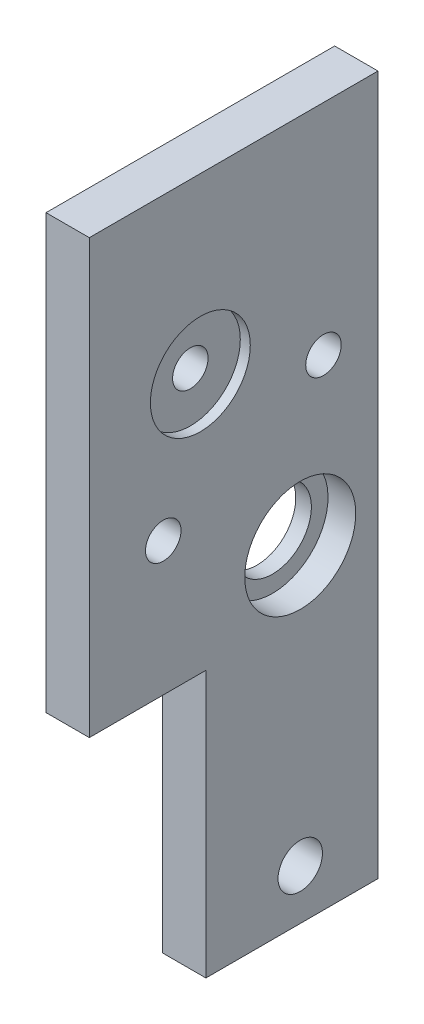
SolidWorks part; units mm, degrees
ref_plane "Front Plane" through (0, 0, 0) normal (0, 0, 1) x (1, 0, 0)
ref_plane "Top Plane" through (0, 0, 0) normal (0, 1, 0) x (1, 0, 0)
ref_plane "Right Plane" through (0, 0, 0) normal (1, 0, 0) x (0, 0, -1)
sketch "Sketch1" plane through (0, 0, 0) normal (1, 0, 0) x (0, 0, -1)
  line L1 (0, 0) -> (-30, 0)
  line L2 (0, 0) -> (0, 63)
  line L3 (0, 63) -> (-30, 63)
  line L4 (-30, 0) -> (-30, 63)
  dimension "D1" = 30
  dimension "D2" = 63
extrude "Boss-Extrude1" add sketch "Sketch1" against normal blind 4
sketch "Sketch2" plane through (0, 0, 0) normal (1, 0, 0) x (0, 0, -1)
  line L0 (-30, 0) -> (0, 0) construction
  line L1 (0, 0) -> (0, 63) construction
  circle A0 centre (-7, 29.5) radius 5
  dimension "D1" = 10
  dimension "D2" = 29.5
  dimension "D3" = 7
extrude "Cut-Extrude1" cut sketch "Sketch2" against normal through all
sketch "Sketch4" [suppressed] plane through (0, 0, 0) normal (1, 0, 0) x (0, 0, -1)
  line L0 (0, 0) -> (0, 57) construction
  line L1 (-15.3544, 38.7) -> (-2.5009, 45.879)
  line L2 (-2.5009, 45.879) -> (-15.1448, 53.421)
  line L3 (-15.1448, 53.421) -> (-15.3544, 38.7)
  circle A0 centre (-11, 46) radius 4.25 construction
  circle A1 centre (-7, 27) radius 5 construction
  dimension "D2" = 19
  dimension "D1" = 8.5
  dimension "D3" = 11
hole_wizard "M4x0.7 Tapped Hole1" [suppressed] positions "3DSketch2" profile "Sketch6" tap size "M4x0.7" standard "ANSI Metric"
sketch3d "3DSketch2" [suppressed]
  point P0 (0, 38.7, 15.3544)
  point P3 (0, 45.879, 2.5009)
  point P6 (0, 53.421, 15.1448)
sketch "Sketch6" plane through (0, 38.7, 15.3544) normal (0, 1, 0) x (0, 0, -1)
  line L0 (0, 0) -> (0, 4)
  line L1 (0, 4) -> (1.05, 4)
  line L3 (1.05, 4) -> (1.05, 2)
  line L4 (1.05, 2) -> (1.65, 2)
  line L5 (1.65, 2) -> (1.65, 0)
  line L7 (1.65, 0) -> (0, 0)
  line L11 (0, -6.35) -> (0, 107.95) construction
  dimension "Thru Tap Drill Dia." = 2.1
  dimension "Thru Tap Drill Depth" = 4
  dimension "Thread Major Dia." = 3.3
  dimension "Thread Depth" = 2
sketch "Sketch7" [suppressed] plane through (-4, 0, 0) normal (-1, 0, 0) x (0, 0, 1)
  line L1 (15.3544, 38.7) -> (15.1448, 53.421)
  line L2 (15.1448, 53.421) -> (2.5009, 45.879)
  line L3 (2.5009, 45.879) -> (15.3544, 38.7)
  circle A0 centre (11, 46) radius 4.25 construction
hole_wizard "CBORE for M3 Pan Head Machine Screw1" [suppressed] positions "3DSketch3" profile "Sketch8" counterbore size "M3" standard "ANSI Metric"
sketch3d "3DSketch3" [suppressed]
  point P0 (-4, 46, 11)
sketch "Sketch8" plane through (-4, 46, 11) normal (0, 1, 0) x (0, 0, 1)
  line L0 (0, 0) -> (0, 4)
  line L1 (0, 4) -> (1.6, 4)
  line L3 (1.6, 4) -> (1.6, 1)
  line L4 (1.6, 1) -> (5.1, 1)
  line L5 (5.1, 1) -> (5.1, 0)
  line L7 (5.1, 0) -> (0, 0)
  line L11 (0, -6.35) -> (0, 107.95) construction
  dimension "Thru Hole Dia." = 3.2
  dimension "Thru Hole Depth" = 4
  dimension "C'Bore Dia." = 10.2
  dimension "C'Bore Depth" = 1
sketch "Sketch10" plane through (0, 0, 0) normal (1, 0, 0) x (0, 0, -1)
  line L0 (0, 0) -> (0, 63) construction
  line L1 (-30, 0) -> (0, 0) construction
  circle A0 centre (-7, 4.5) radius 2
  dimension "D1" = 4
  dimension "D2" = 7
  dimension "D3" = 4.5
hole_wizard "Ø4.0 (4) Diameter Hole1" positions "3DSketch4" profile "Sketch11" hole size "Ø4.0" standard "ANSI Metric" end condition through all
sketch3d "3DSketch4"
  point P0 (0, 4.5, 7)
sketch "Sketch11" plane through (0, 4.5, 7) normal (0, 1, 0) x (0, 0, -1)
  line L0 (0, 0) -> (0, 4)
  line L1 (0, 4) -> (2, 4)
  line L2 (2, 4) -> (2, 0)
  line L5 (2, 0) -> (0, 0)
  line L11 (0, -6.35) -> (0, 107.95) construction
  dimension "Thru Hole Dia." = 4
  dimension "Thru Hole Depth" = 4
sketch "Sketch12" plane through (0, 0, 0) normal (1, 0, 0) x (0, 0, -1)
  line L1 (-30, 0) -> (-15.5, 0)
  line L2 (-30, 0) -> (-30, 24)
  line L3 (-30, 24) -> (-15.5, 24)
  line L4 (-15.5, 0) -> (-15.5, 24)
  dimension "D1" = 14.5
  dimension "D2" = 24
extrude "Cut-Extrude2" cut sketch "Sketch12" against normal through all
mirror "Mirror7" about plane through (0, 0, 0) normal (1, 0, 0) of "Cut-Extrude2", "Cut-Extrude1", "Boss-Extrude1"
sketch "Sketch13" plane through (-4, 0, 0) normal (-1, 0, 0) x (0, 0, 1)
  line L0 (0, 63) -> (30, 63) construction
  line L1 (-5.8164, 63) -> (36.8572, 63)
  line L2 (-5.8164, 63) -> (-5.8164, -2.7798)
  line L3 (-5.8164, -2.7798) -> (36.8572, -2.7798)
  line L4 (36.8572, 63) -> (36.8572, -2.7798)
extrude "Cut-Extrude5" cut sketch "Sketch13" against normal blind 4
sketch "Sketch30" plane through (0, 0, 0) normal (-1, 0, 0) x (0, 0, 1)
  line L0 (0, 0) -> (0, 63) construction
  line L1 (15.5, 0) -> (0, 0) construction
  circle A0 centre (7, 4.5) radius 2
  dimension "D1" = 4
  dimension "D2" = 7
  dimension "D3" = 4.5
hole_wizard "Ø4.0 (4) Diameter Hole6" positions "3DSketch19" profile "Sketch31" hole size "Ø4.0" standard "ANSI Metric" end condition through all
sketch3d "3DSketch19"
  point P0 (0, 4.5, 7)
sketch "Sketch31" plane through (0, 4.5, 7) normal (0, 1, 0) x (0, 0, 1)
  line L0 (0, 0) -> (0, 4)
  line L1 (0, 4) -> (2, 4)
  line L2 (2, 4) -> (2, 0)
  line L5 (2, 0) -> (0, 0)
  line L11 (0, -6.35) -> (0, 107.95) construction
  dimension "Thru Hole Dia." = 4
  dimension "Thru Hole Depth" = 4
sketch "Sketch32" [suppressed] plane through (4, 0, 0) normal (1, 0, 0) x (0, 0, -1)
  line L1 (-2.5009, 45.879) -> (-15.1448, 53.421)
  line L2 (-15.1448, 53.421) -> (-15.3544, 38.7)
  line L3 (-15.3544, 38.7) -> (-2.5009, 45.879)
  circle A0 centre (-11, 46) radius 4.25 construction
  dimension "D1" = 8.5
hole_wizard "CBORE for M3 Pan Head Machine Screw6" [suppressed] positions "3DSketch21" profile "Sketch34" counterbore size "M3" standard "ANSI Metric"
sketch3d "3DSketch21" [suppressed]
  point P0 (4, 46, 11)
sketch "Sketch34" plane through (4, 46, 11) normal (0, 1, 0) x (0, 0, -1)
  line L0 (0, 0) -> (0, 4)
  line L1 (0, 4) -> (1.6, 4)
  line L3 (1.6, 4) -> (1.6, 1)
  line L4 (1.6, 1) -> (5.1, 1)
  line L5 (5.1, 1) -> (5.1, 0)
  line L7 (5.1, 0) -> (0, 0)
  line L11 (0, -6.35) -> (0, 107.95) construction
  dimension "Thru Hole Dia." = 3.2
  dimension "Thru Hole Depth" = 4
  dimension "C'Bore Dia." = 10.2
  dimension "C'Bore Depth" = 1
sketch "Sketch35" [suppressed] plane through (0, 0, 0) normal (-1, 0, 0) x (0, 0, 1)
  line L1 (15.3544, 38.7) -> (15.1448, 53.421)
  line L2 (15.1448, 53.421) -> (2.5009, 45.879)
  line L3 (2.5009, 45.879) -> (15.3544, 38.7)
  circle A0 centre (11, 46) radius 4.25 construction
  dimension "D1" = 8.5
hole_wizard "M4x0.7 Tapped Hole3" [suppressed] positions "3DSketch28" profile "Sketch40" tap size "M4x0.7" standard "ANSI Metric"
sketch3d "3DSketch28" [suppressed]
  point P0 (0, 45.879, 2.5009)
  point P3 (0, 53.421, 15.1448)
  point P6 (0, 38.7, 15.3544)
sketch "Sketch40" plane through (0, 45.879, 2.5009) normal (0, 1, 0) x (0, 0, 1)
  line L0 (0, 0) -> (0, 4)
  line L1 (0, 4) -> (1.05, 4)
  line L3 (1.05, 4) -> (1.05, 2)
  line L4 (1.05, 2) -> (1.65, 2)
  line L5 (1.65, 2) -> (1.65, 0)
  line L7 (1.65, 0) -> (0, 0)
  line L11 (0, -6.35) -> (0, 107.95) construction
  dimension "Thru Tap Drill Dia." = 2.1
  dimension "Thru Tap Drill Depth" = 4
  dimension "Thread Major Dia." = 3.3
  dimension "Thread Depth" = 2
sketch "Sketch41" plane through (4, 0, 0) normal (1, 0, 0) x (0, 0, -1)
  line L0 (0, 0) -> (0, 63) construction
  circle A0 centre (-16, 47.3606) radius 1.5
  circle A1 centre (-7, 29.5) radius 5 construction
  dimension "D1" = 3
  dimension "D2" = 20
  dimension "D3" = 16
hole_wizard "CBORE for M3 Pan Head Machine Screw7" positions "3DSketch29" profile "Sketch42" counterbore size "M3" standard "ANSI Metric" end condition through all
sketch3d "3DSketch29"
  point P0 (4, 47.3606, 16)
sketch "Sketch42" plane through (4, 47.3606, 16) normal (0, 1, 0) x (0, 0, -1)
  line L0 (0, 0) -> (0, 4)
  line L1 (0, 4) -> (1.6, 4)
  line L3 (1.6, 4) -> (1.6, 1)
  line L4 (1.6, 1) -> (4.5, 1)
  line L5 (4.5, 1) -> (4.5, 0)
  line L7 (4.5, 0) -> (0, 0)
  line L11 (0, -6.35) -> (0, 107.95) construction
  dimension "Thru Hole Dia." = 3.2
  dimension "Thru Hole Depth" = 4
  dimension "C'Bore Dia." = 9
  dimension "C'Bore Depth" = 1
sketch "Sketch43" plane through (0, 0, 0) normal (-1, 0, 0) x (0, 0, 1)
  line L0 (16, 47.3606) -> (7, 29.5) construction
  circle A0 centre (19.3397, 36.0326) radius 1.5
  circle A1 centre (4.9083, 43.3046) radius 1.5
  dimension "D1" = 3
  dimension "D2" = 8.08
  dimension "D3" = 11.81
hole_wizard "CSK for M3 Flat Head Machine Screw1" positions "3DSketch30" profile "Sketch44" countersink size "M3" standard "ANSI Metric" end condition through all
sketch3d "3DSketch30"
  point P0 (0, 36.0326, 19.3397)
  point P3 (0, 43.3046, 4.9083)
sketch "Sketch44" plane through (0, 36.0326, 19.3397) normal (0, 1, 0) x (0, 0, 1)
  line L0 (0, 0) -> (0, 4)
  line L1 (0, 4) -> (1.6, 4)
  line L2 (1.6, 4) -> (1.6, 0.4)
  line L3 (1.6, 0.4) -> (2, 0)
  line L5 (2, 0) -> (0, 0)
  line L6 (-1.6, 0.4) -> (-2, 0) construction
  line L11 (0, -6.35) -> (0, 107.95) construction
  dimension "Thru Hole Dia." = 3.2
  dimension "Thru Hole Depth" = 4
  dimension "Near C'Sink Dia." = 4
  dimension "Near C'Sink Angle" = 90
sketch "Sketch45" plane through (4, 0, 0) normal (1, 0, 0) x (0, 0, -1)
  line L0 (-30, 63) -> (-30, 24)
  line L1 (-30, 63) -> (-26, 63)
  line L2 (-30, 24) -> (-26, 24)
  line L3 (-26, 63) -> (-26, 24)
  dimension "D1" = 4
extrude "Cut-Extrude6" cut sketch "Sketch45" against normal through all both and the other way through all
sketch "Sketch46" plane through (0, 0, 0) normal (0, 0, -1) x (-1, 0, 0)
  line L0 (-4, 63) -> (-3.9, 63)
  line L1 (0, 63) -> (-4, 63) construction
  line L2 (-3.9, 63) -> (-3.9, 0)
  line L3 (0, 0) -> (-4, 0) construction
  line L4 (-3.9, 0) -> (-4, 0)
  line L5 (-4, 0) -> (-4, 63)
extrude "Cut-Extrude7" cut sketch "Sketch46" against normal through all
sketch "Sketch47" plane through (0, 0, 0) normal (-1, 0, 0) x (0, 0, 1)
  circle A0 centre (7, 29.5) radius 5
  circle A1 centre (7, 29.5) radius 3.5
  dimension "D1" = 10
  dimension "D2" = 7
extrude "Boss-Extrude2" add sketch "Sketch47" against normal blind 1.4
